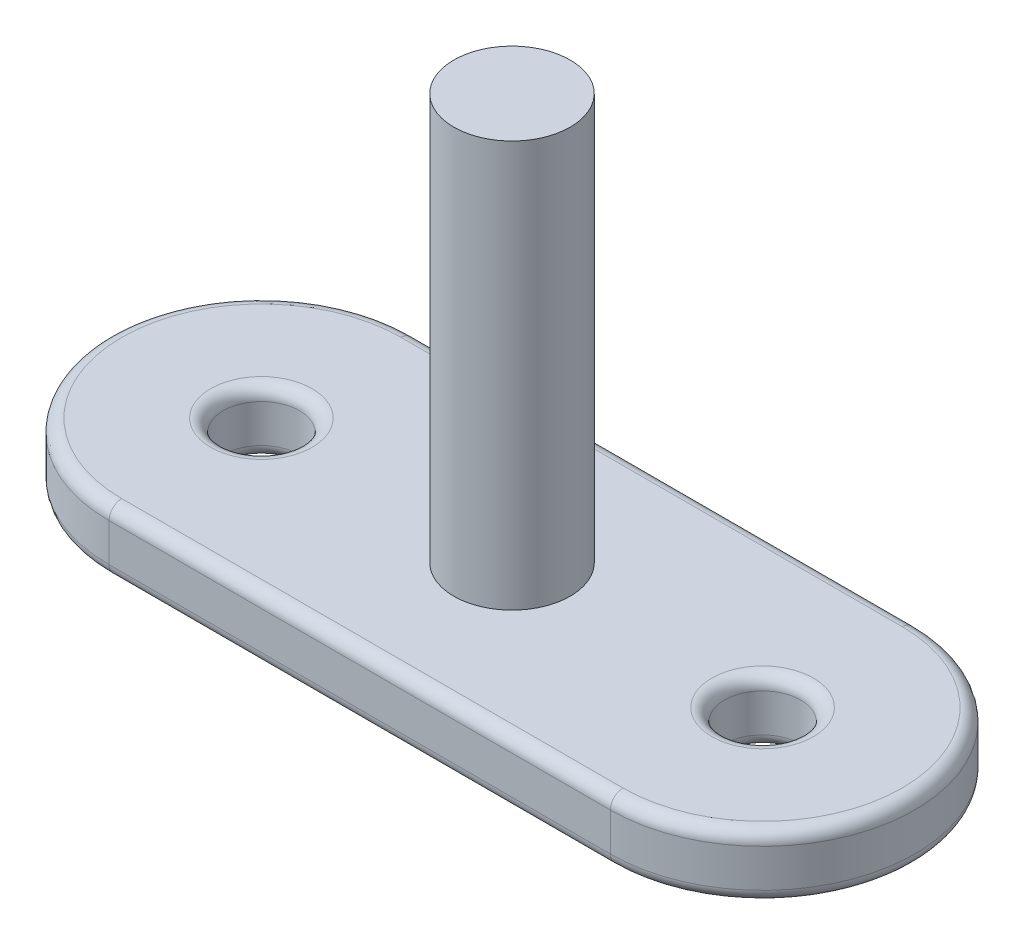
SolidWorks part; units mm, degrees
ref_plane "Front Plane" through (0, 0, 0) normal (0, 0, 1) x (1, 0, 0)
ref_plane "Top Plane" through (0, 0, 0) normal (0, 1, 0) x (1, 0, 0)
ref_plane "Right Plane" through (0, 0, 0) normal (1, 0, 0) x (0, 0, -1)
sketch "Sketch1" plane through (0, 0, 0) normal (0, 1, 0) x (1, 0, 0)
  line L0 (-9.87, 0) -> (9.87, 0) construction
  line L1 (-9.87, 6) -> (9.87, 6)
  line L2 (-9.87, -6) -> (9.87, -6)
  circle A0 centre (-9.87, 0) radius 1.5
  circle A1 centre (9.87, 0) radius 1.5
  arc A2 (-9.87, 6) -> (-9.87, -6) centre (-9.87, 0) ccw
  arc A3 (9.87, -6) -> (9.87, 6) centre (9.87, 0) ccw
  dimension "D1" = 3
  dimension "D2" = 3
  dimension "D4" = 12
  dimension "D5" = 12
  dimension "D3" = 19.74
extrude "Boss-Extrude1" add sketch "Sketch1" along normal blind 2.5
fillet "Fillet1" radius 0.5 12 edges at (9.87, 2.5, 1.5) (0, 2.5, -6) (15.87, 2.5, 0) (0, 2.5, 6) (-15.87, 2.5, 0) (-9.87, 2.5, 1.5) (9.87, 0, 1.5) (-9.87, 0, 1.5) (0, 0, 6) (15.87, 0, 0) (0, 0, -6) (-15.87, 0, 0)
sketch "Sketch2" plane through (0, 2.5, 0) normal (0, 1, 0) x (1, 0, 0)
  circle A0 centre (0, 0) radius 2.2915
extrude "Boss-Extrude2" add sketch "Sketch2" along normal blind 16
